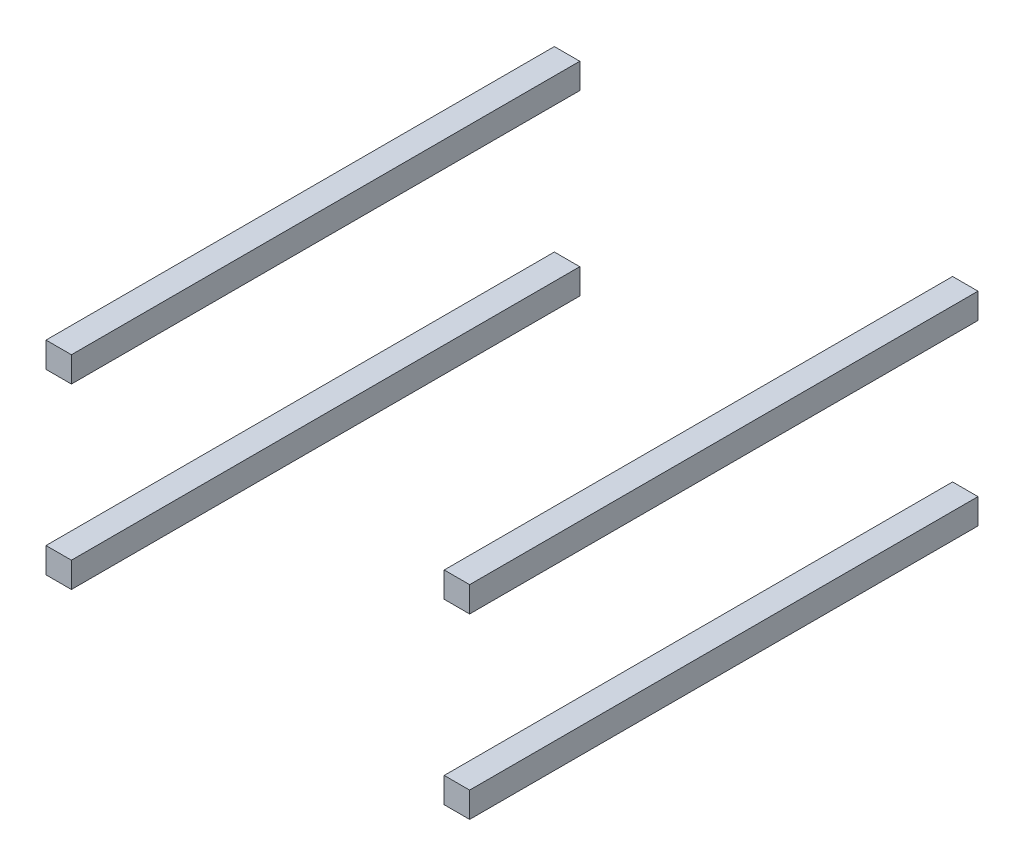
SolidWorks part; units mm, degrees
ref_plane "前视基准面" through (0, 0, 0) normal (0, 0, 1) x (1, 0, 0)
ref_plane "上视基准面" through (0, 0, 0) normal (0, 1, 0) x (1, 0, 0)
ref_plane "右视基准面" through (0, 0, 0) normal (1, 0, 0) x (0, 0, -1)
other "Configuration Table"
sketch "草图1" plane through (0, 0, 0) normal (0, 0, 1) x (1, 0, 0)
  line L1 (-447.6984, 45.5808) -> (-417.6984, 45.5808)
  line L2 (-447.6984, 45.5808) -> (-447.6984, 15.5808)
  line L3 (-447.6984, 15.5808) -> (-417.6984, 15.5808)
  line L4 (-417.6984, 45.5808) -> (-417.6984, 15.5808)
  line L5 (22.3016, 45.5808) -> (52.3016, 45.5808)
  line L6 (22.3016, 45.5808) -> (22.3016, 15.5808)
  line L7 (22.3016, 15.5808) -> (52.3016, 15.5808)
  line L8 (52.3016, 45.5808) -> (52.3016, 15.5808)
  line L9 (-447.6984, -164.4192) -> (-417.6984, -164.4192)
  line L10 (-447.6984, -164.4192) -> (-447.6984, -194.4192)
  line L11 (-447.6984, -194.4192) -> (-417.6984, -194.4192)
  line L12 (-417.6984, -164.4192) -> (-417.6984, -194.4192)
  line L13 (22.3016, -164.4192) -> (52.3016, -164.4192)
  line L14 (22.3016, -164.4192) -> (22.3016, -194.4192)
  line L15 (22.3016, -194.4192) -> (52.3016, -194.4192)
  line L16 (52.3016, -164.4192) -> (52.3016, -194.4192)
  dimension "D1" = 30
  dimension "D2" = 440
  dimension "D3" = 180
extrude "凸台-拉伸1" add sketch "草图1" along normal blind 600 contours L9 L12 L11 L10 | L13 L16 L15 L14 | L5 L8 L7 L6 | L1 L4 L3 L2
